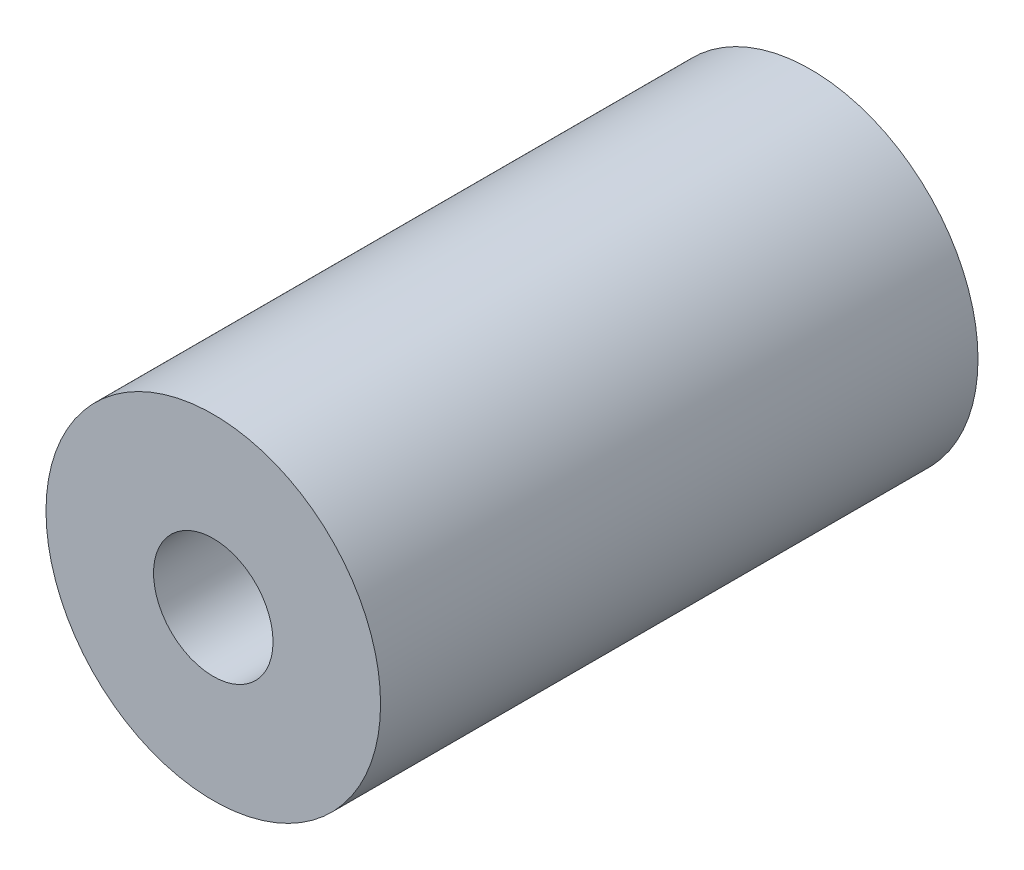
SolidWorks part; units mm, degrees
ref_plane "前视基准面" through (0, 0, 0) normal (0, 0, 1) x (1, 0, 0)
ref_plane "上视基准面" through (0, 0, 0) normal (0, 1, 0) x (1, 0, 0)
ref_plane "右视基准面" through (0, 0, 0) normal (1, 0, 0) x (0, 0, -1)
sketch "草图1" plane through (0, 0, 0) normal (0, 0, 1) x (1, 0, 0)
  circle A0 centre (0, 0) radius 2.5
  circle A1 centre (0, 0) radius 7
  dimension "D1" = 5
  dimension "D2" = 14
extrude "凸台-拉伸1" add sketch "草图1" along normal blind 25
